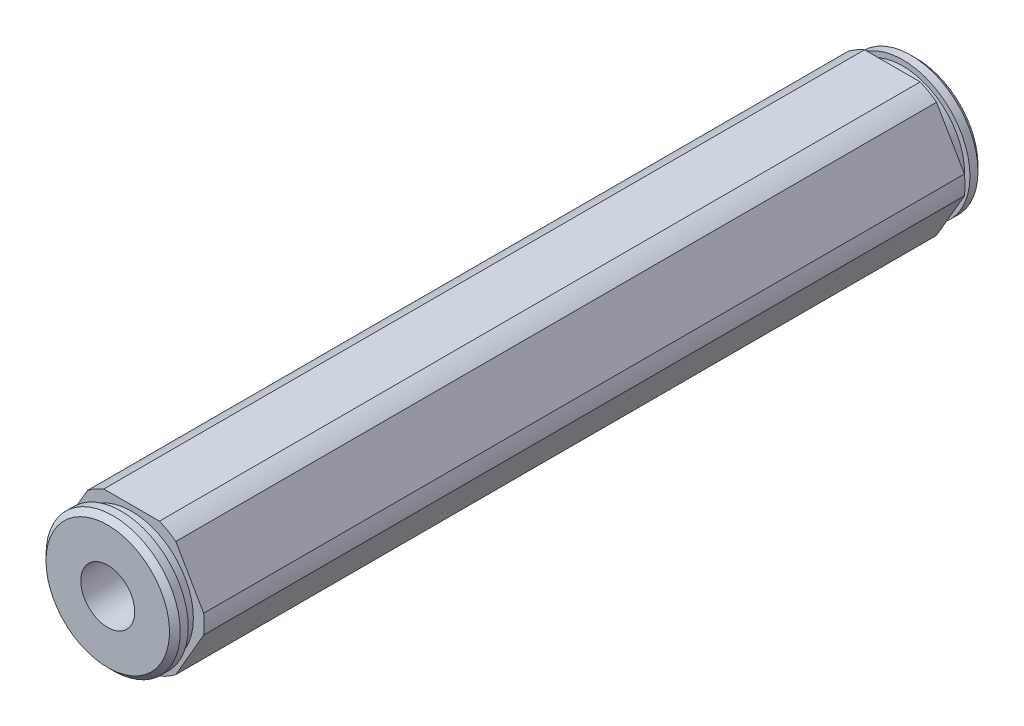
SolidWorks part; units mm, degrees
material "6061-T6 (SS)"
ref_plane "Front Plane" through (0, 0, 0) normal (0, 0, 1) x (1, 0, 0)
ref_plane "Top Plane" through (0, 0, 0) normal (0, 1, 0) x (1, 0, 0)
ref_plane "Right Plane" through (0, 0, 0) normal (1, 0, 0) x (0, 0, -1)
sketch "Sketch2" plane through (0, 0, 0) normal (1, 0, 0) x (0, 0, -1)
  line L0 (1.27, 6.35) -> (1.27, 5.842)
  line L1 (0, 0) -> (76.5048, 0)
  line L2 (0, 0) -> (0, 6.35)
  line L3 (0, 6.35) -> (1.27, 6.35)
  line L4 (76.5048, 0) -> (76.5048, 6.35)
  line L5 (1.27, 5.842) -> (2.2606, 5.842)
  line L6 (2.2606, 5.842) -> (2.2606, 7.62)
  line L7 (2.2606, 7.62) -> (74.2442, 7.62)
  line L8 (75.2348, 6.35) -> (76.5048, 6.35)
  line L9 (75.2348, 6.35) -> (75.2348, 5.842)
  line L10 (75.2348, 5.842) -> (74.2442, 5.842)
  line L11 (74.2442, 5.842) -> (74.2442, 7.62)
  line L12 (74.93, 0) -> (91.6439, 0) construction
  dimension "D2" = 71.9836
  dimension "D3" = 1.27
  dimension "D5" = 7.62
  dimension "D7" = 6.35
  dimension "D8" = 0.9906
  dimension "D10" = 11.684
revolve "Revolve1" add sketch "Sketch2" angle 360 about L1
sketch "Sketch3" plane through (0, 0, 0) normal (0, 0, 1) x (1, 0, 0)
  line L19 (6.8168, 0.893) -> (4.1818, 5.457)
  line L20 (2.635, 6.35) -> (-2.635, 6.35)
  line L21 (-4.1818, 5.457) -> (-6.8168, 0.893)
  line L22 (-6.8168, -0.893) -> (-4.1818, -5.457)
  line L23 (-2.635, -6.35) -> (2.635, -6.35)
  line L24 (4.1818, -5.457) -> (6.8168, -0.893)
  circle A0 centre (0, 0) radius 6.35 construction
  circle A19 centre (0, 0) radius 7.62
  circle A20 centre (0, 0) radius 7.62 construction
  arc A21 (-2.635, 6.35) -> (-4.1818, 5.457) centre (0, 0) ccw
  arc A22 (4.1818, 5.457) -> (2.635, 6.35) centre (0, 0) ccw
  arc A23 (6.8168, -0.893) -> (6.8168, 0.893) centre (0, 0) ccw
  arc A24 (2.635, -6.35) -> (4.1818, -5.457) centre (0, 0) ccw
  arc A25 (-4.1818, -5.457) -> (-2.635, -6.35) centre (0, 0) ccw
  arc A26 (-6.8168, 0.893) -> (-6.8168, -0.893) centre (0, 0) ccw
  dimension "D1" = 12.7
  dimension "D2" = 13.75
extrude "Cut-Extrude1" cut sketch "Sketch3" against normal up to surface (76.5048 mm away) up to face at (6.35, 0, -76.5048)
sketch "Sketch4" plane through (0, 0, -76.5048) normal (0, 0, -1) x (-1, 0, 0)
  circle A0 centre (0, 0) radius 2.5527
  dimension "D1" = 5.1054
extrude "Cut-Extrude2" cut sketch "Sketch4" against normal up to surface (76.5048 mm away) up to face at (6.35, 0, 0)
chamfer "Chamfer1" distance 0.508 angle 45 2 edges at (6.35, 0, 0) (6.35, 0, -76.5048)
